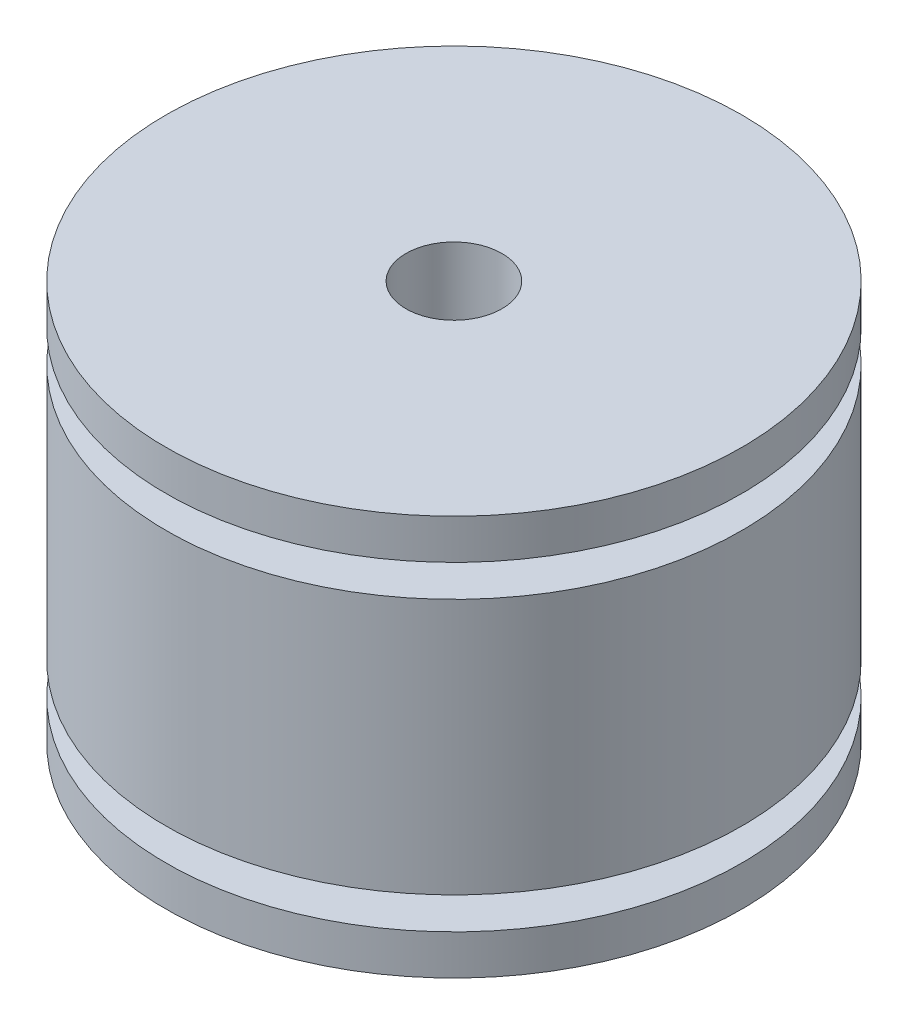
SolidWorks part; units mm, degrees
ref_plane "Front Plane" through (0, 0, 0) normal (0, 0, 1) x (1, 0, 0)
ref_plane "Top Plane" through (0, 0, 0) normal (0, 1, 0) x (1, 0, 0)
ref_plane "Right Plane" through (0, 0, 0) normal (1, 0, 0) x (0, 0, -1)
sketch "Sketch1" plane through (0, 0, 0) normal (0, 0, 1) x (1, 0, 0)
  line L0 (0, 0) -> (0, 28.5001) construction
  line L1 (0, 0) -> (10, 0) construction
  line L3 (10, 0) -> (18, 0)
  line L7 (18, 25) -> (0, 25) construction
  line L9 (18, 25) -> (3, 25)
  line L10 (3, 25) -> (3, 0)
  line L11 (3, 0) -> (10, 0)
  line L12 (18, 0) -> (18, 2.5)
  line L13 (18, 2.5) -> (15, 2.5)
  line L14 (15, 2.5) -> (15, 4.5)
  line L15 (15, 4.5) -> (18, 4.5)
  line L16 (18, 4.5) -> (18, 20.5)
  line L17 (18, 20.5) -> (15, 20.5)
  line L18 (15, 20.5) -> (15, 22.5)
  line L19 (15, 22.5) -> (18, 22.5)
  line L20 (18, 22.5) -> (18, 25)
  line L21 (18, 12.5) -> (3, 12.5) construction
  point P20 (0, 0)
  point P21 (0, 0)
  point P22 (0, 0)
  point P23 (0, 0)
  point P24 (10, 0.5176)
  dimension "D1" = 3
  dimension "D2" = 16
  dimension "D3" = 2.5
  dimension "D4" = 2
  dimension "D5" = 15
  dimension "D6" = 3
revolve "Revolve1" add sketch "Sketch1" angle 360 about L0
sketch "Sketch2" plane through (0, 0, 0) normal (0, 0, 1) x (1, 0, 0)
  line L0 (0, 0) -> (0, 25) construction
  line L1 (3, 25) -> (-3, 25) construction
  circle A0 centre (0, 12.5) radius 1.65
  point P7 (0, 14.192)
  point P8 (0, 19.3361)
  point P9 (0, 12.5)
  dimension "D1" = 3.3
extrude "Cut-Extrude1" cut sketch "Sketch2" against normal through all
